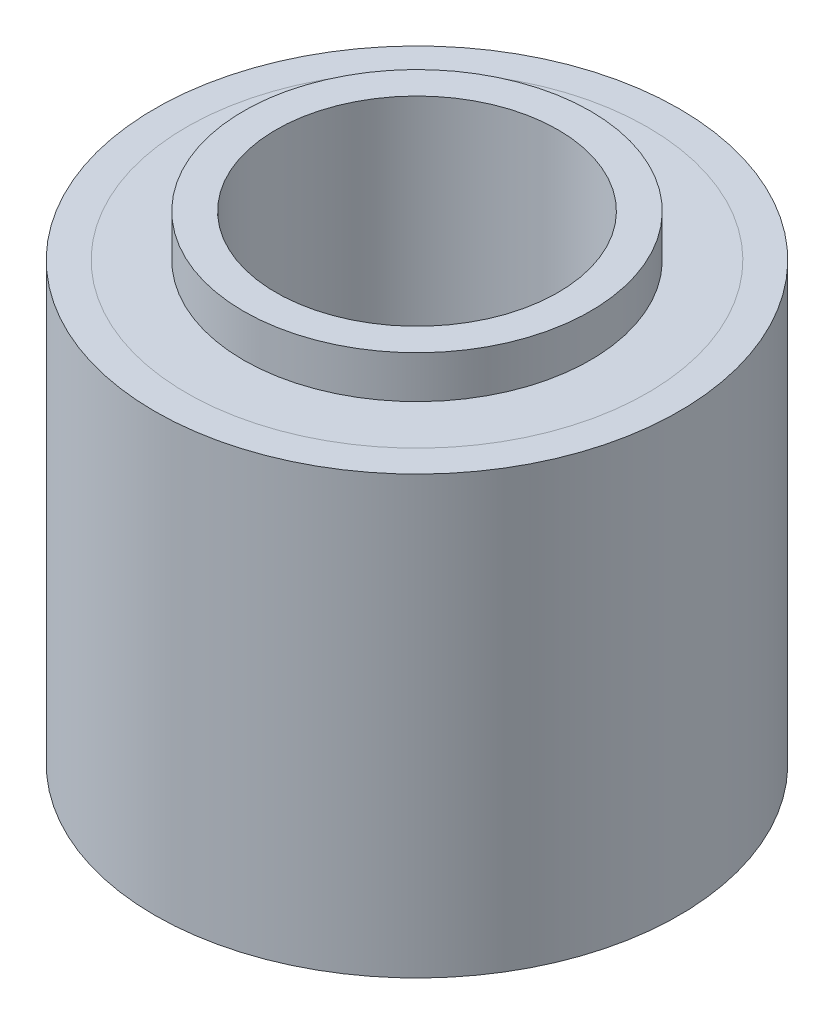
SolidWorks part; units mm, degrees
material "1060 Alaşım"
ref_plane "Ön Düzlem" through (0, 0, 0) normal (0, 0, 1) x (1, 0, 0)
ref_plane "Üst Düzlem" through (0, 0, 0) normal (0, 1, 0) x (1, 0, 0)
ref_plane "Sağ Düzlem" through (0, 0, 0) normal (1, 0, 0) x (0, 0, -1)
sketch "Çizim1" plane through (0, 0, 0) normal (0, 0, 1) x (1, 0, 0)
  line L0 (0, 0) -> (0, 83.1407) construction
  line L1 (8.66, 0) -> (10.65, 0)
  line L2 (8.66, 0) -> (8.66, 29.4)
  line L3 (8.66, 29.4) -> (10.65, 29.4)
  line L4 (10.65, 0) -> (10.65, 29.4)
  line L6 (14.15, 0) -> (16.1, 0)
  line L7 (14.15, 0) -> (14.15, 26.8)
  line L8 (14.15, 26.8) -> (16.1, 26.8)
  line L9 (16.1, 0) -> (16.1, 26.8)
  dimension "D1" = 8.66
  dimension "D2" = 10.65
  dimension "D3" = 29.4
  dimension "D4" = 26.8
  dimension "D5" = 14.15
  dimension "D6" = 16.1
revolve "Döndür1" add sketch "Çizim1" angle 360 about L0
sketch "Çizim4" plane through (0, 0, 0) normal (0, 0, 1) x (1, 0, 0)
  line L0 (-10.65, 0) -> (10.65, 0) construction
  line L1 (10.65, 0) -> (14.15, 0)
  line L2 (10.65, 0) -> (10.65, 26.8)
  line L3 (10.65, 26.8) -> (14.15, 26.8)
  line L4 (14.15, 0) -> (14.15, 26.8)
  line L5 (-14.15, 0) -> (14.15, 0) construction
  line L6 (14.15, 26.8) -> (-14.15, 26.8) construction
  line L7 (0, 0) -> (0, 29.4) construction
  line L8 (8.66, 29.4) -> (-8.66, 29.4) construction
revolve "Döndür3" add sketch "Çizim4" angle 360 about L7
